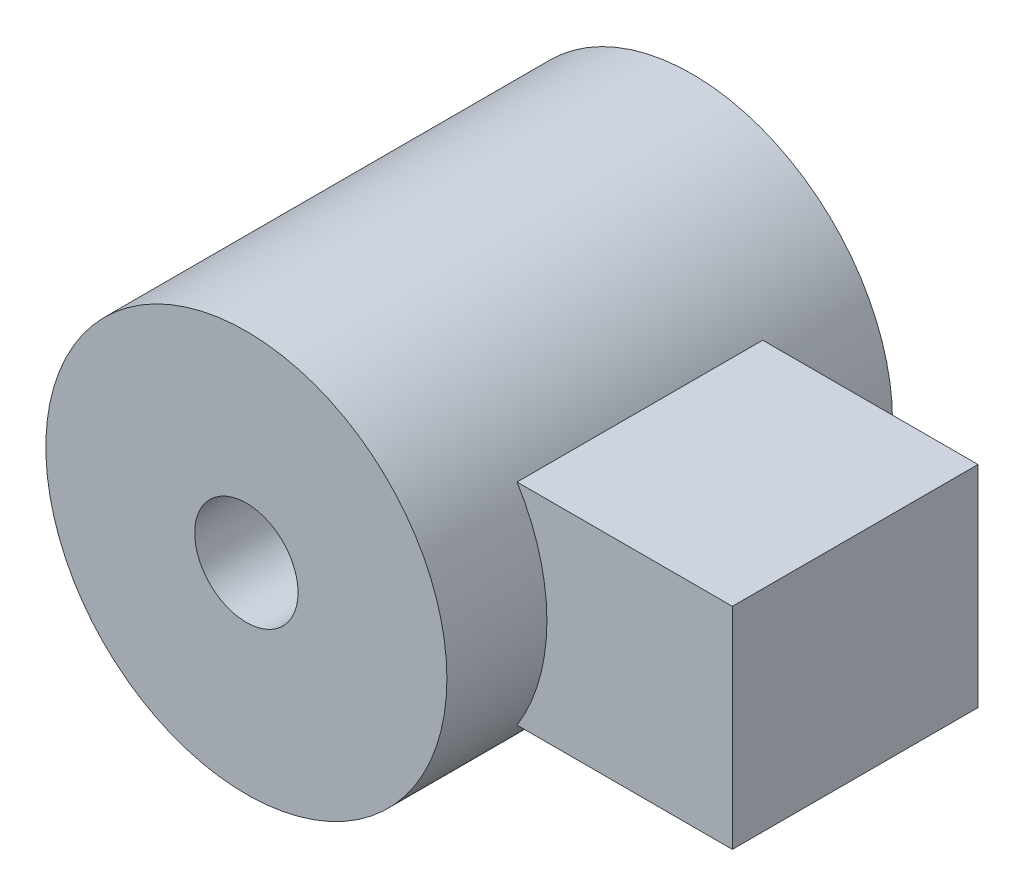
SolidWorks part; units mm, degrees
material "7075-T6 (SN)"
ref_plane "Front Plane" through (0, 0, 0) normal (0, 0, 1) x (1, 0, 0)
ref_plane "Top Plane" through (0, 0, 0) normal (0, 1, 0) x (1, 0, 0)
ref_plane "Right Plane" through (0, 0, 0) normal (1, 0, 0) x (0, 0, -1)
sketch "Sketch1" plane through (0, 0, 0) normal (0, 0, 1) x (1, 0, 0)
  circle A0 centre (0, 0) radius 5.715
  dimension "D1" = 11.43
extrude "Boss-Extrude1" add sketch "Sketch1" along normal blind 12.7
sketch "Sketch2" plane through (0, 0, 12.7) normal (0, 0, 1) x (1, 0, 0)
  circle A0 centre (0, 0) radius 1.4732
  dimension "D1" = 2.9464
extrude "Cut-Extrude1" cut sketch "Sketch2" against normal through all
chamfer "Chamfer1" [suppressed] distance 1 angle 70
chamfer "Chamfer3" [suppressed] distance 1 angle 70
ref_plane "Plane2" through (4, 0, 0) normal (1, 0, 0) x (0, 0, -1)
sketch "Sketch3" plane through (4, 0, 0) normal (1, 0, 0) x (0, 0, -1)
  line L0 (6.2865, 0) -> (-6.2865, 0) construction
  line L1 (-9.85, 3) -> (-2.85, 3)
  line L2 (-9.85, 3) -> (-9.85, -3)
  line L3 (-9.85, -3) -> (-2.85, -3)
  line L4 (-2.85, 3) -> (-2.85, -3)
  line L5 (-9.85, 3) -> (-2.85, -3) construction
  line L6 (-9.85, -3) -> (-2.85, 3) construction
  line L7 (0, 6.2865) -> (0, -6.2865) construction
  point P0 (-6.35, 0)
  dimension "D1" = 6.35
  dimension "D2" = 6
  dimension "D3" = 7
extrude "Boss-Extrude2" add sketch "Sketch3" along normal blind 7
fillet "Fillet1" [suppressed] radius 1
equation "\"FrangiboltTotalDiameter\"= 0.450in"
equation "\"FrangiboltTotalLength\"= 0.500in"
equation "\"FrangiboltThruHoleDiameter\"= 0.116in"
equation "\"D1@Sketch1\"=\"FrangiboltTotalDiameter\""
equation "\"D1@Boss-Extrude1\"=\"FrangiboltTotalLength\""
equation "\"D1@Sketch2\"=\"FrangiboltThruHoleDiameter\""
equation "\"D1@Sketch3\"=\"FrangiboltTotalLength\"/2"
